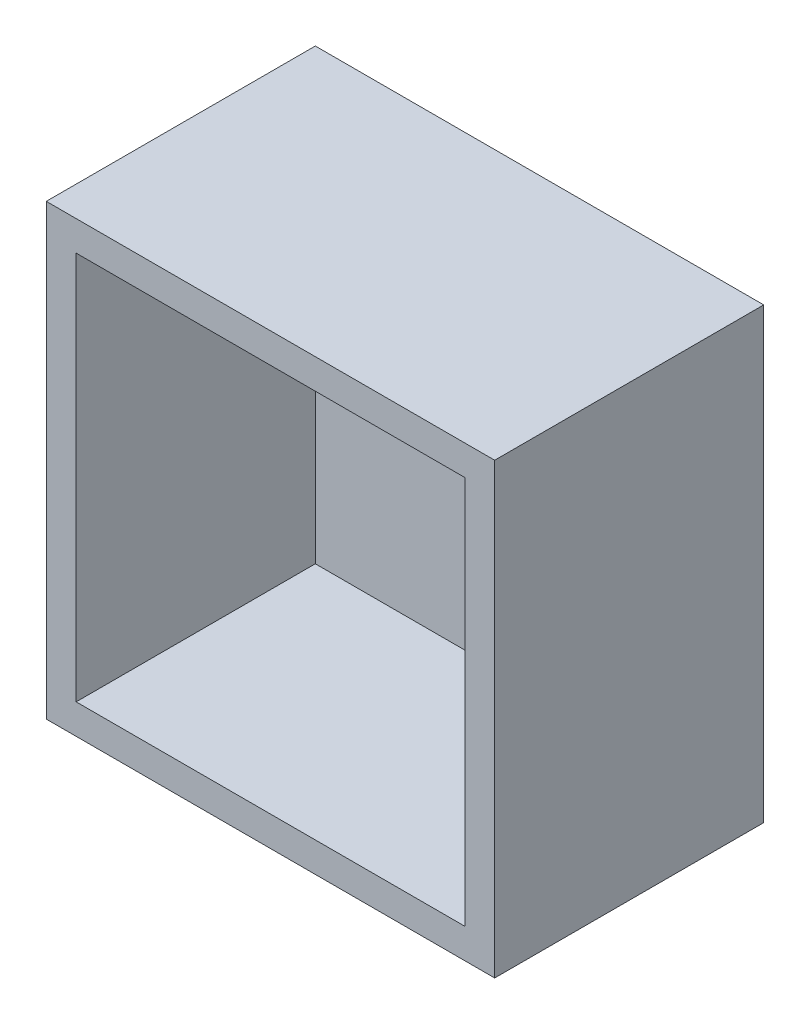
SolidWorks part; units mm, degrees
material "PET"
ref_plane "Front Plane" through (0, 0, 0) normal (0, 0, 1) x (1, 0, 0)
ref_plane "Top Plane" through (0, 0, 0) normal (0, 1, 0) x (1, 0, 0)
ref_plane "Right Plane" through (0, 0, 0) normal (1, 0, 0) x (0, 0, -1)
sketch "Sketch2" plane through (0, 0, 0) normal (0, 0, 1) x (1, 0, 0)
  line L5 (-37.5, -37.5) -> (37.5, -37.5)
  line L6 (-37.5, -37.5) -> (-37.5, 37.5)
  line L7 (-37.5, 37.5) -> (37.5, 37.5)
  line L8 (37.5, -37.5) -> (37.5, 37.5)
  line L9 (-37.5, -37.5) -> (37.5, 37.5) construction
  line L10 (-37.5, 37.5) -> (37.5, -37.5) construction
  point P0 (0, 0)
  dimension "D1" = 75
  dimension "D2" = 75
extrude "Boss-Extrude1" add sketch "Sketch2" along normal blind 45
shell "Shell1" thickness 5
